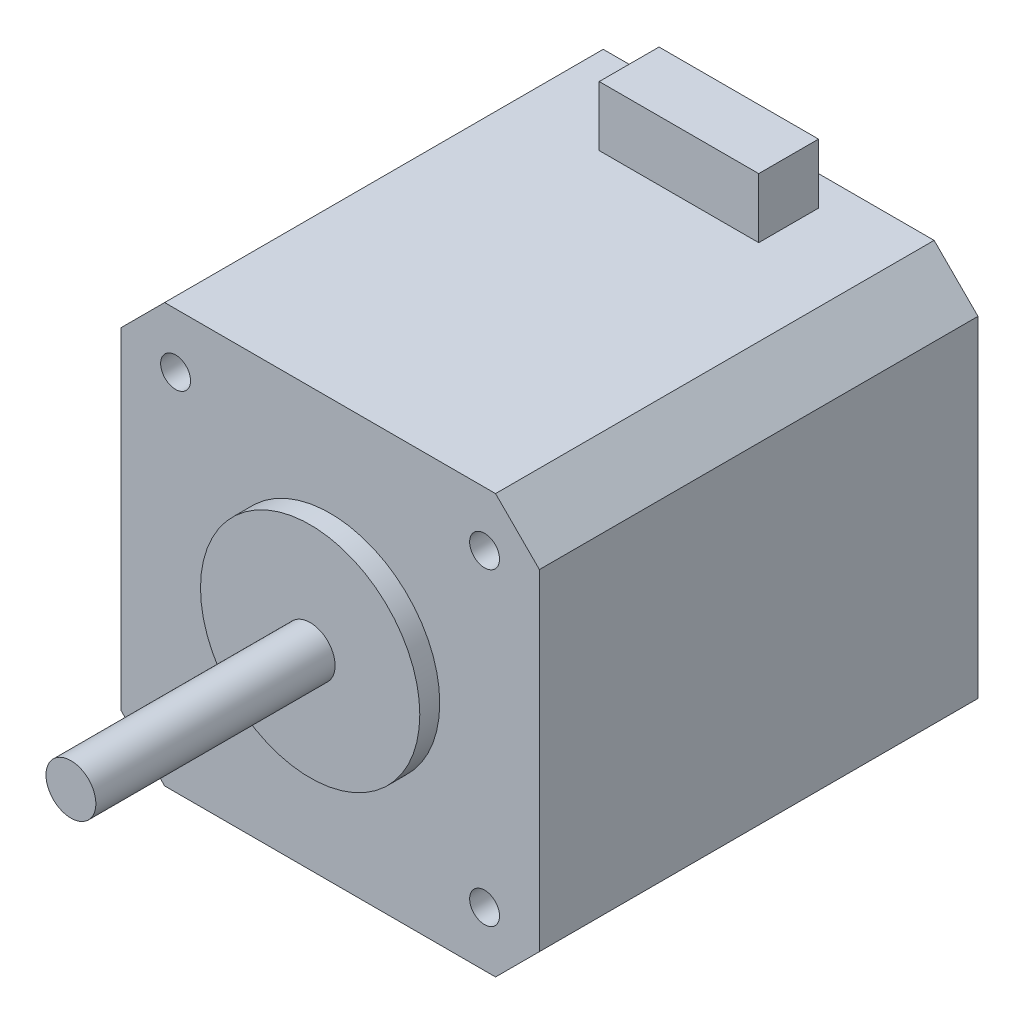
SolidWorks part; units mm, degrees
ref_plane "前视基准面" through (0, 0, 0) normal (0, 0, 1) x (1, 0, 0)
ref_plane "上视基准面" through (0, 0, 0) normal (0, 1, 0) x (1, 0, 0)
ref_plane "右视基准面" through (0, 0, 0) normal (1, 0, 0) x (0, 0, -1)
sketch "草图1" plane through (0, 0, 0) normal (0, 0, 1) x (1, 0, 0)
  line L0 (0, 0) -> (31.3879, 0) construction
  line L1 (0, 0) -> (0, 21.2989) construction
  line L2 (21, 0) -> (21, 16.6)
  line L3 (16.6, 21) -> (0, 21)
  line L4 (21, 16.6) -> (16.6, 21)
  line L5 (0, -21) -> (16.6, -21)
  line L6 (16.6, -21) -> (21, -16.6)
  line L7 (21, -16.6) -> (21, 0)
  line L8 (-21, 0) -> (-21, -16.6)
  line L9 (-21, -16.6) -> (-16.6, -21)
  line L10 (-16.6, -21) -> (0, -21)
  line L11 (0, 21) -> (-16.6, 21)
  line L12 (-16.6, 21) -> (-21, 16.6)
  line L13 (-21, 16.6) -> (-21, 0)
  circle A0 centre (15.5, 15.5) radius 1.5
  circle A1 centre (15.5, -15.5) radius 1.5
  circle A2 centre (-15.5, -15.5) radius 1.5
  circle A3 centre (-15.5, 15.5) radius 1.5
  point P5 (21, 21)
  point P32 (0, 0)
  dimension "D5" = 3
  dimension "D1" = 42
  dimension "D2" = 42
  dimension "D3" = 31
  dimension "D4" = 31
  dimension "D6" = 4
extrude "凸台-拉伸1" add sketch "草图1" along normal blind 44
sketch "草图2" plane through (0, 0, 44) normal (0, 0, 1) x (1, 0, 0)
  circle A0 centre (0, 0) radius 11
  dimension "D1" = 22
extrude "凸台-拉伸2" add sketch "草图2" along normal blind 2 contours A0
sketch "草图3" plane through (0, 0, 44) normal (0, 0, 1) x (1, 0, 0)
  circle A0 centre (0, 0) radius 2.5
  dimension "D1" = 5
extrude "凸台-拉伸3" add sketch "草图3" along normal blind 26
sketch "草图4" plane through (0, 21, 0) normal (0, 1, 0) x (1, 0, 0)
  line L0 (-8, -9) -> (8, -9)
  line L1 (16.6, 0) -> (-16.6, 0) construction
  line L2 (0, 0) -> (0, 3.5781) construction
  line L3 (-8, -9) -> (-8, -3)
  line L4 (-8, -3) -> (8, -3)
  line L5 (8, -3) -> (8, -9)
  dimension "D1" = 9
  dimension "D2" = 8
  dimension "D3" = 8
  dimension "D4" = 3
extrude "凸台-拉伸4" add sketch "草图4" along normal blind 6 contours L5 L0 L3 L4
